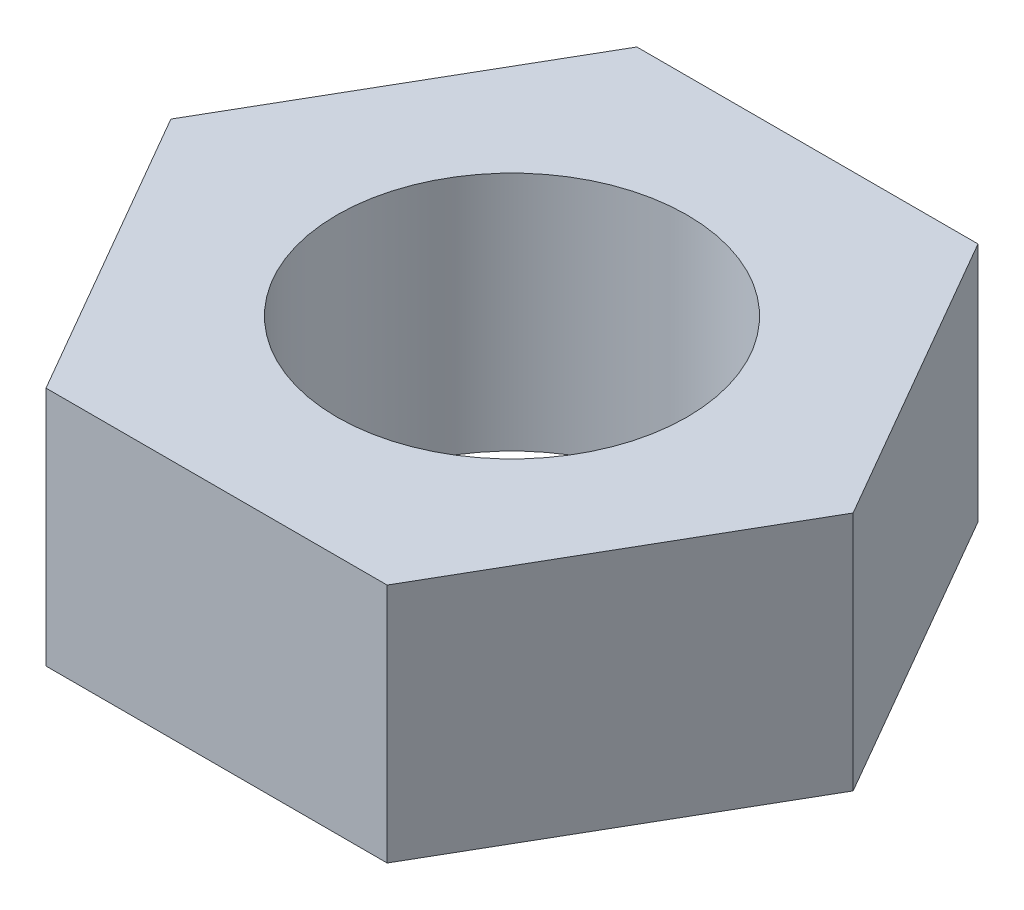
SolidWorks part; units mm, degrees
material "1060 Alloy"
ref_plane "Front Plane" through (0, 0, 0) normal (0, 0, 1) x (1, 0, 0)
ref_plane "Top Plane" through (0, 0, 0) normal (0, 1, 0) x (1, 0, 0)
ref_plane "Right Plane" through (0, 0, 0) normal (1, 0, 0) x (0, 0, -1)
sketch "Sketch1" plane through (0, 0, 0) normal (0, 1, 0) x (1, 0, 0)
  line L1 (7.7942, 0) -> (3.8971, 6.75)
  line L2 (3.8971, 6.75) -> (-3.8971, 6.75)
  line L3 (-3.8971, 6.75) -> (-7.7942, 0)
  line L4 (-7.7942, 0) -> (-3.8971, -6.75)
  line L5 (-3.8971, -6.75) -> (3.8971, -6.75)
  line L6 (3.8971, -6.75) -> (7.7942, 0)
  circle A0 centre (0, 0) radius 6.75 construction
  circle A1 centre (0, 0) radius 4
  dimension "D1" = 13.5
  dimension "D2" = 8
extrude "Boss-Extrude1" add sketch "Sketch1" along normal blind 5.5
